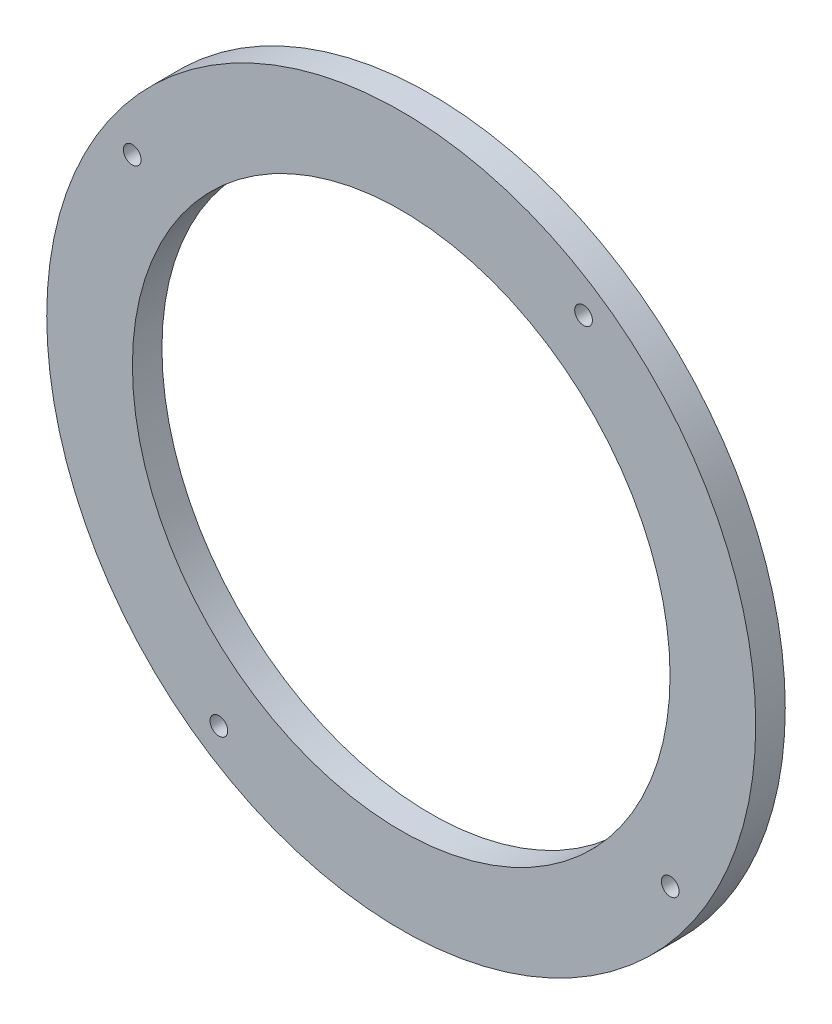
SolidWorks part; units mm, degrees
ref_plane "前视基准面" through (0, 0, 0) normal (0, 0, 1) x (1, 0, 0)
ref_plane "上视基准面" through (0, 0, 0) normal (0, 1, 0) x (1, 0, 0)
ref_plane "右视基准面" through (0, 0, 0) normal (1, 0, 0) x (0, 0, -1)
sketch "草图1" plane through (0, 0, 0) normal (0, 0, 1) x (1, 0, 0)
  circle A0 centre (0, 0) radius 45.5
  circle A1 centre (0, 0) radius 60
extrude "凸台-拉伸1" add sketch "草图1" along normal blind 5
sketch "草图2" plane through (0, 0, 5) normal (0, 0, 1) x (1, 0, 0)
  circle A0 centre (-30.8599, -45.5265) radius 1.5
  circle A1 centre (-45.5265, 30.8599) radius 1.5
  circle A2 centre (30.8599, 45.5265) radius 1.5
  circle A3 centre (45.5265, -30.8599) radius 1.5
  point P13 (0, 0)
  dimension "D1" = 4
extrude "切除-拉伸1" cut sketch "草图2" against normal blind 5
